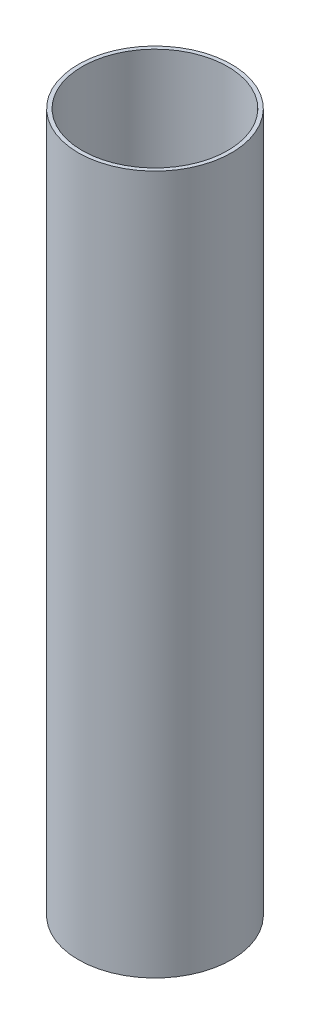
SolidWorks part; units mm, degrees
ref_plane "Front Plane" through (0, 0, 0) normal (0, 0, 1) x (1, 0, 0)
ref_plane "Top Plane" through (0, 0, 0) normal (0, 1, 0) x (1, 0, 0)
ref_plane "Right Plane" through (0, 0, 0) normal (1, 0, 0) x (0, 0, -1)
sketch "Sketch1" plane through (0, 0, 0) normal (0, 1, 0) x (1, 0, 0)
  circle A0 centre (0, 0) radius 32.9
  circle A1 centre (0, 0) radius 31.25
  dimension "D1" = 65.8
  dimension "D2" = 62.5
extrude "Boss-Extrude1" add sketch "Sketch1" along normal blind 300
